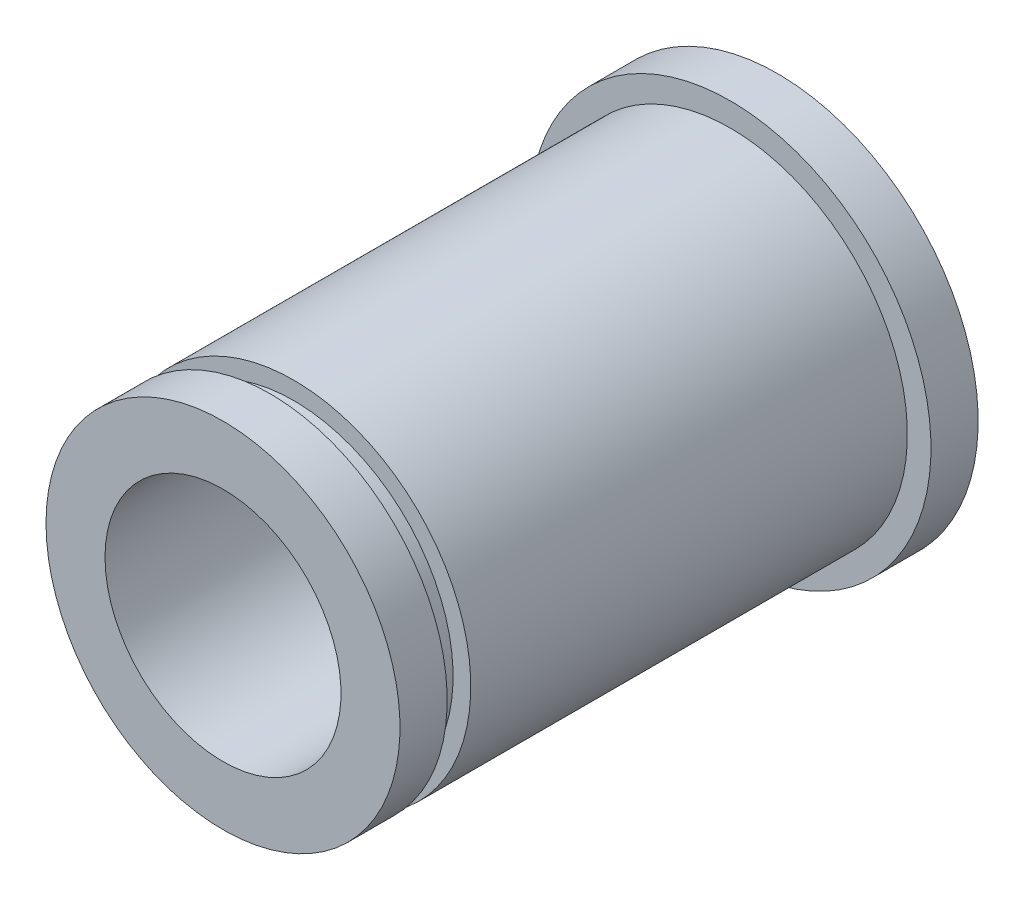
SolidWorks part; units mm, degrees
ref_plane "Front Plane" through (0, 0, 0) normal (0, 0, 1) x (1, 0, 0)
ref_plane "Top Plane" through (0, 0, 0) normal (0, 1, 0) x (1, 0, 0)
ref_plane "Right Plane" through (0, 0, 0) normal (1, 0, 0) x (0, 0, -1)
sketch "Sketch2" plane through (0, 0, 0) normal (0, 1, 0) x (1, 0, 0)
  line L0 (0, 1.4373) -> (0, -2.8703) construction
sketch "Sketch1" plane through (0, 0, 0) normal (0, 1, 0) x (1, 0, 0)
  line L0 (5, 2) -> (5, -21.5)
  line L1 (5, -21.5) -> (7.5, -21.5)
  line L2 (7.5, -21.5) -> (7.5, -19.5)
  line L3 (7.5, -19.5) -> (6.75, -19.5)
  line L4 (6.75, -19.5) -> (6.75, -18.5)
  line L5 (6.75, -18.5) -> (7.5, -18.5)
  line L6 (7.5, -18.5) -> (7.5, 0)
  line L7 (7.5, 0) -> (8.5, 0)
  line L8 (8.5, 0) -> (8.5, 2)
  line L9 (8.5, 2) -> (5, 2)
  line L10 (0, 0) -> (7.5, 0) construction
  dimension "D1" = 7.5
  dimension "D2" = 6.75
  dimension "D3" = 8.5
  dimension "D4" = 5
  dimension "D5" = 1
  dimension "D6" = 2
  dimension "D7" = 23.5
  dimension "D8" = 2
revolve "Revolve1" add sketch "Sketch1" angle 360 about L0
